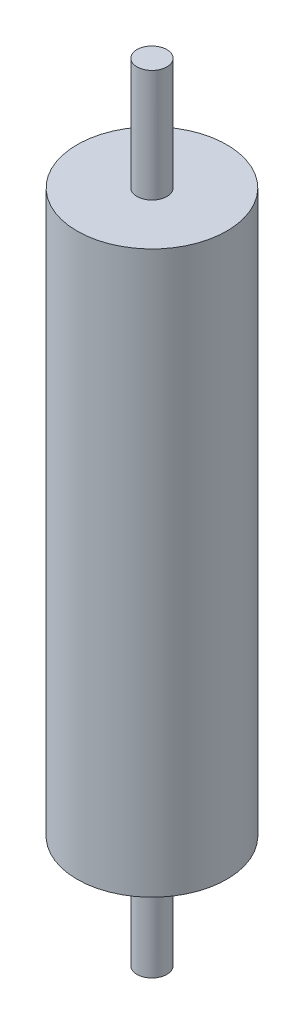
SolidWorks part; units mm, degrees
ref_plane "Front Plane" through (0, 0, 0) normal (0, 0, 1) x (1, 0, 0)
ref_plane "Top Plane" through (0, 0, 0) normal (0, 1, 0) x (1, 0, 0)
ref_plane "Right Plane" through (0, 0, 0) normal (1, 0, 0) x (0, 0, -1)
sketch "Sketch1" plane through (0, 0, 0) normal (0, 1, 0) x (1, 0, 0)
  circle A0 centre (0, 0) radius 20
  dimension "D1" = 40
extrude "Boss-Extrude1" add sketch "Sketch1" along normal blind 150
sketch "Sketch2" plane through (0, 0, 0) normal (0, -1, 0) x (1, 0, 0)
  circle A0 centre (0, 0) radius 4
  dimension "D1" = 8
extrude "Boss-Extrude2" add sketch "Sketch2" along normal blind 30
ref_plane "Plane1" through (0, 75, 0) normal (0, -1, 0) x (-1, 0, 0)
mirror "Mirror1" about plane through (0, 75, 0) normal (0, -1, 0) of "Boss-Extrude2"
